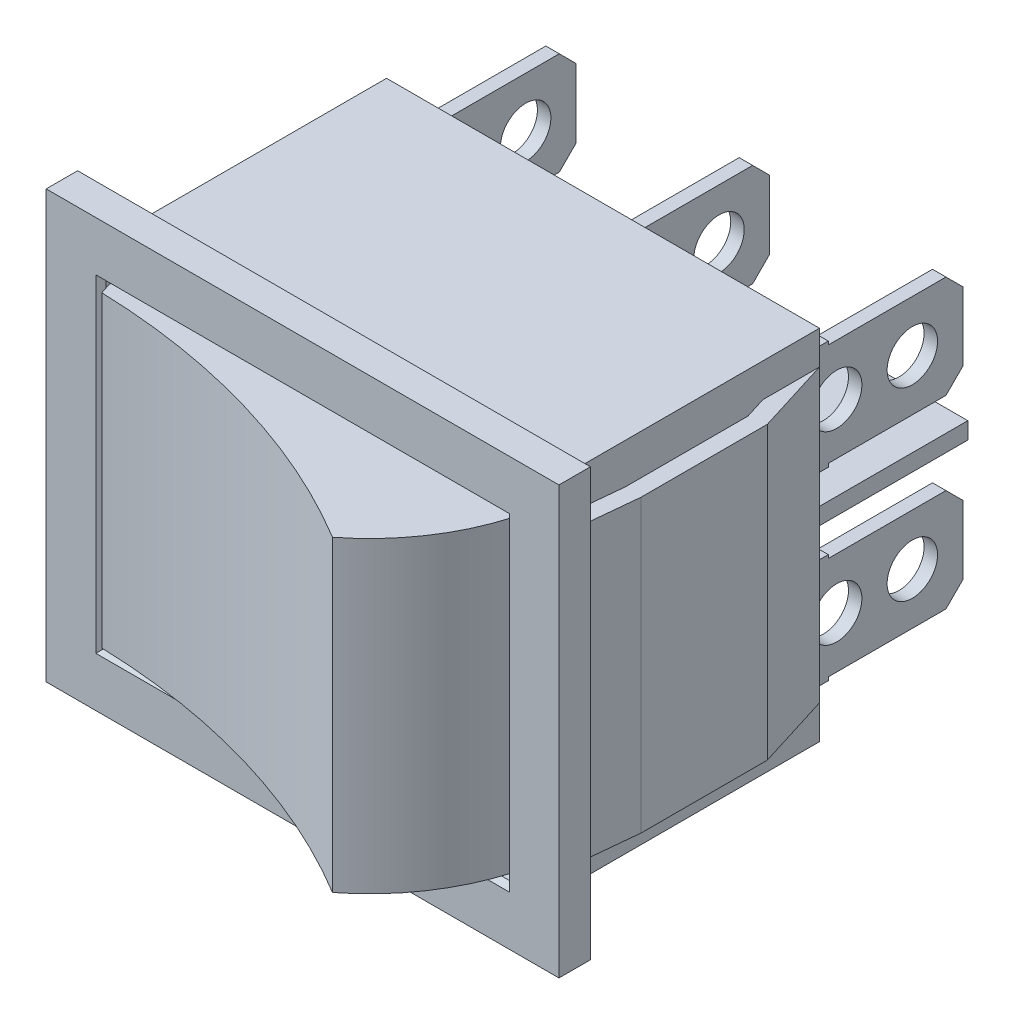
SolidWorks part; units mm, degrees
ref_plane "Front Plane" through (0, 0, 0) normal (0, 0, 1) x (1, 0, 0)
ref_plane "Top Plane" through (0, 0, 0) normal (0, 1, 0) x (1, 0, 0)
ref_plane "Right Plane" through (0, 0, 0) normal (1, 0, 0) x (0, 0, -1)
sketch "Sketch1" plane through (0, 0, 0) normal (0, 0, 1) x (1, 0, 0)
  line L1 (-12.875, 10.65) -> (12.875, 10.65)
  line L2 (-12.875, 10.65) -> (-12.875, -10.65)
  line L3 (-12.875, -10.65) -> (12.875, -10.65)
  line L4 (12.875, 10.65) -> (12.875, -10.65)
  line L5 (-12.875, 10.65) -> (12.875, -10.65) construction
  line L6 (-12.875, -10.65) -> (12.875, 10.65) construction
  point P0 (0, 0)
  dimension "D1" = 21.3
  dimension "D2" = 25.75
extrude "Boss-Extrude1" add sketch "Sketch1" along normal blind 16
sketch "Sketch3" plane through (0, 0, 16) normal (0, 0, 1) x (1, 0, 0)
  line L1 (-15.25, 12.7) -> (15.25, 12.7)
  line L2 (-15.25, 12.7) -> (-15.25, -12.7)
  line L3 (-15.25, -12.7) -> (15.25, -12.7)
  line L4 (15.25, 12.7) -> (15.25, -12.7)
  line L5 (-15.25, 12.7) -> (15.25, -12.7) construction
  line L6 (-15.25, -12.7) -> (15.25, 12.7) construction
  point P0 (0, 0)
  dimension "D1" = 25.4
  dimension "D2" = 30.5
extrude "Boss-Extrude3" add sketch "Sketch3" along normal blind 1.87
sketch "Sketch4" plane through (0, 0, 0) normal (0, 0, -1) x (-1, 0, 0)
  line L1 (-11.9, 0.5) -> (11.9, 0.5)
  line L2 (-11.9, 0.5) -> (-11.9, -0.5)
  line L3 (-11.9, -0.5) -> (11.9, -0.5)
  line L4 (11.9, 0.5) -> (11.9, -0.5)
  line L5 (-11.9, 0.5) -> (11.9, -0.5) construction
  line L6 (-11.9, -0.5) -> (11.9, 0.5) construction
  point P0 (0, 0)
  dimension "D1" = 1
  dimension "D2" = 23.8
extrude "Boss-Extrude4" add sketch "Sketch4" along normal blind 9.8
sketch "Sketch5" plane through (0, 0, 0) normal (0, 0, -1) x (-1, 0, 0)
  line L0 (-11.9, -0.5) -> (11.9, -0.5) construction
  line L1 (11.1, -2.25) -> (11.9, -2.25)
  line L2 (11.1, -2.25) -> (11.1, -8.75)
  line L3 (11.1, -8.75) -> (11.9, -8.75)
  line L4 (11.9, -2.25) -> (11.9, -8.75)
  line L5 (11.1, -2.25) -> (11.9, -8.75) construction
  line L6 (11.1, -8.75) -> (11.9, -2.25) construction
  line L7 (-0.4, -8.75) -> (0.4, -8.75)
  line L8 (-0.4, -8.75) -> (-0.4, -2.25)
  line L9 (-0.4, -2.25) -> (0.4, -2.25)
  line L10 (0.4, -8.75) -> (0.4, -2.25)
  line L11 (-0.4, -8.75) -> (0.4, -2.25) construction
  line L12 (-0.4, -2.25) -> (0.4, -8.75) construction
  line L13 (-11.9, -2.25) -> (-11.1, -2.25)
  line L14 (-11.9, -2.25) -> (-11.9, -8.75)
  line L15 (-11.9, -8.75) -> (-11.1, -8.75)
  line L16 (-11.1, -2.25) -> (-11.1, -8.75)
  line L17 (-11.9, -2.25) -> (-11.1, -8.75) construction
  line L18 (-11.9, -8.75) -> (-11.1, -2.25) construction
  point P0 (11.5, -5.5)
  point P5 (-11.5, -5.5)
  point P6 (0, -5.5)
  dimension "D1" = 6.5
  dimension "D2" = 0.8
  dimension "D3" = 6.5
  dimension "D4" = 0.8
  dimension "D5" = 6.5
  dimension "D6" = 0.8
  dimension "D7" = 5
extrude "Boss-Extrude5" add sketch "Sketch5" along normal blind 9.5
sketch "Sketch6" plane through (11.9, 0, 0) normal (1, 0, 0) x (0, 0, -1)
  line L1 (9.5, -2.25) -> (1.5, -2.25)
  line L2 (9.5, -2.25) -> (9.5, -2.45)
  line L3 (9.5, -2.45) -> (1.5, -2.45)
  line L4 (1.5, -2.25) -> (1.5, -2.45)
  line L5 (9.5, -8.75) -> (1.5, -8.75)
  line L6 (9.5, -8.75) -> (9.5, -8.55)
  line L7 (9.5, -8.55) -> (1.5, -8.55)
  line L8 (1.5, -8.75) -> (1.5, -8.55)
  dimension "D1" = 0.2
  dimension "D2" = 8
extrude "Cut-Extrude1" cut sketch "Sketch6" against normal through all
chamfer "Chamfer1" distance 1 angle 45 6 edges at (-11.5, -8.55, -9.5) (-11.5, -2.45, -9.5) (0, -8.55, -9.5) (0, -2.45, -9.5) (11.5, -2.45, -9.5) (11.5, -8.55, -9.5)
sketch "Sketch7" plane through (11.9, 0, 0) normal (1, 0, 0) x (0, 0, -1)
  line L0 (1.5, -2.25) -> (0, -2.25) construction
  line L1 (9.5, -3.45) -> (9.5, -7.55) construction
  circle A0 centre (6.5, -5.5) radius 1.5
  circle A1 centre (2, -5.5) radius 1.5
  dimension "D1" = 3.25
  dimension "D2" = 3
  dimension "D3" = 3
  dimension "D4" = 4.5
extrude "Cut-Extrude2" cut sketch "Sketch7" against normal through all
ref_plane "Plane1" through (0, 0, 0) normal (0, -1, 0) x (-1, 0, 0)
mirror "Mirror1" about plane through (0, 0, 0) normal (0, -1, 0) of "Cut-Extrude2", "Chamfer1", "Cut-Extrude1", "Boss-Extrude5"
sketch "Sketch8" plane through (0, 10.65, 0) normal (0, 1, 0) x (1, 0, 0)
  line L0 (-12.875, 0) -> (-14.275, -4.5)
  line L1 (-12.875, -16) -> (-12.875, 0) construction
  line L2 (-14.275, -4.5) -> (-14.275, -12)
  line L3 (-14.275, -12) -> (-13.8799, -16)
  line L4 (15.25, -16) -> (-15.25, -16) construction
  line L5 (-13.8799, -16) -> (-12.875, -16)
  line L6 (-12.875, -16) -> (-13.275, -11.9507)
  line L7 (-13.275, -11.9507) -> (-13.275, -4.652)
  line L8 (-13.275, -4.652) -> (-12.875, -3.3662)
  line L9 (-12.875, -3.3662) -> (-12.875, 0)
  line L10 (12.875, 0) -> (-12.875, 0) construction
  line L11 (12.875, -16) -> (-12.875, -16) construction
  dimension "D1" = 1
  dimension "D2" = 1
  dimension "D3" = 1
  dimension "D4" = 1.4
  dimension "D5" = 4.5
  dimension "D6" = 4
extrude "Boss-Extrude6" add sketch "Sketch8" against normal offset from surface (17.3 mm away) 2 from offset 2 up to face at (0, -10.65, 8) offset against normal yes
ref_plane "Plane2" through (0, 0, 0) normal (-1, 0, 0) x (0, 0, 1)
mirror "Mirror2" about plane through (0, 0, 0) normal (-1, 0, 0) of "Boss-Extrude6"
sketch "Sketch9" plane through (0, 0, 17.87) normal (0, 0, 1) x (1, 0, 0)
  line L0 (-12, -9.45) -> (-12, 9.45)
  line L1 (-15.25, -12.7) -> (15.25, -12.7)
  line L2 (-15.25, -12.7) -> (-15.25, 12.7)
  line L3 (-15.25, 12.7) -> (15.25, 12.7)
  line L4 (15.25, -12.7) -> (15.25, 12.7)
  line L5 (-12, 9.45) -> (12, 9.45)
  line L6 (12, -9.45) -> (12, 9.45)
  line L7 (-12, -9.45) -> (12, -9.45)
  dimension "D1" = 3.25
extrude "Cut-Extrude3" cut sketch "Sketch9" against normal blind 5 contours L0 L7 L6 L5
sketch "Sketch10" plane through (0, 0, 0) normal (0, -1, 0) x (-1, 0, 0)
  line L0 (15.25, -17.87) -> (-15.25, -17.87) construction
  circle A0 centre (0, -13.87) radius 12.5
  dimension "D1" = 4
  dimension "D2" = 25
extrude "Boss-Extrude7" add sketch "Sketch10" along normal mid plane 18.3
sketch "Sketch11" plane through (0, 0, 0) normal (0, -1, 0) x (-1, 0, 0)
  circle A0 centre (13, -58) radius 40
  dimension "D1" = 80
  dimension "D2" = 58
  dimension "D3" = 13
extrude "Cut-Extrude4" cut sketch "Sketch11" against normal through all both and the other way through all
chamfer "Chamfer2" distance 0.3 angle 45 4 edges at (0, -9.45, 17.87) (12, 0, 17.87) (0, 9.45, 17.87) (-12, 0, 17.87)
sketch "Sketch12" plane through (0, 0, 0) normal (0, 0, 1) x (1, 0, 0)
  line L1 (15, -10.85) -> (-15, -10.85)
  line L2 (15, -10.85) -> (15, 10.85)
  line L3 (15, 10.85) -> (-15, 10.85)
  line L4 (-15, -10.85) -> (-15, 10.85)
  line L5 (15, -10.85) -> (-15, 10.85) construction
  line L6 (15, 10.85) -> (-15, -10.85) construction
  point P0 (0, 0)
  dimension "D1" = 30
  dimension "D2" = 21.7
